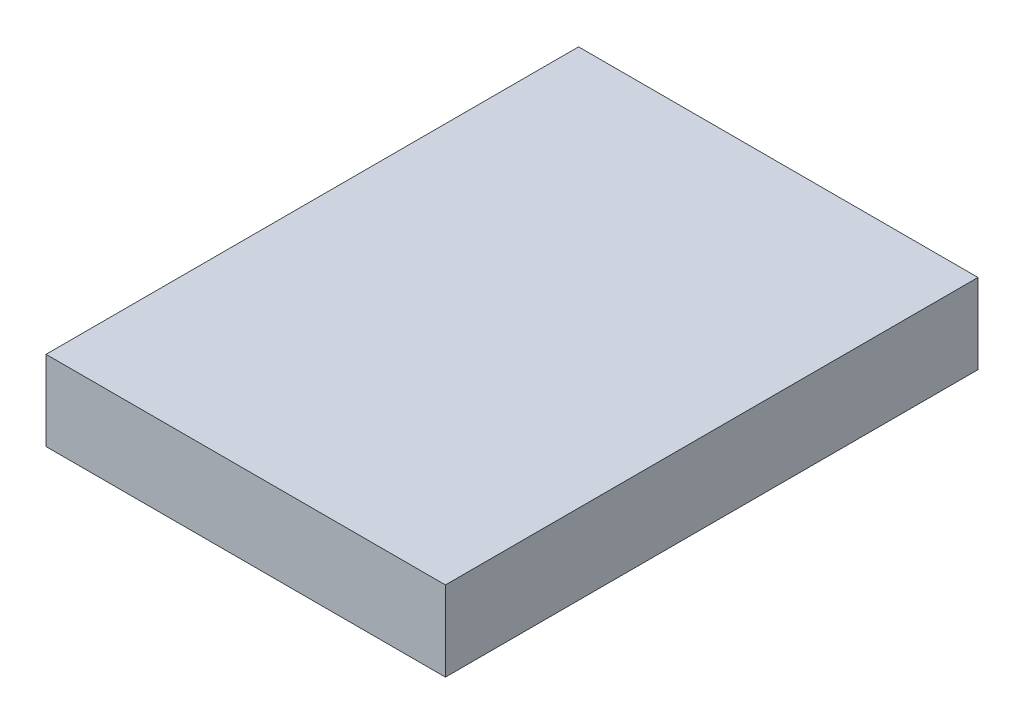
SolidWorks part; units mm, degrees
ref_plane "Front Plane" through (0, 0, 0) normal (0, 0, 1) x (1, 0, 0)
ref_plane "Top Plane" through (0, 0, 0) normal (0, 1, 0) x (1, 0, 0)
ref_plane "Right Plane" through (0, 0, 0) normal (1, 0, 0) x (0, 0, -1)
sketch "Sketch1" plane through (0, 0, 0) normal (0, 0, 1) x (1, 0, 0)
  line L1 (-37.5, 7.5) -> (37.5, 7.5)
  line L2 (-37.5, 7.5) -> (-37.5, -7.5)
  line L3 (-37.5, -7.5) -> (37.5, -7.5)
  line L4 (37.5, 7.5) -> (37.5, -7.5)
  line L5 (-37.5, 7.5) -> (37.5, -7.5) construction
  line L6 (-37.5, -7.5) -> (37.5, 7.5) construction
  point P0 (0, 0)
  dimension "D1" = 15
  dimension "D2" = 75
extrude "Boss-Extrude1" add sketch "Sketch1" along normal mid plane 100
